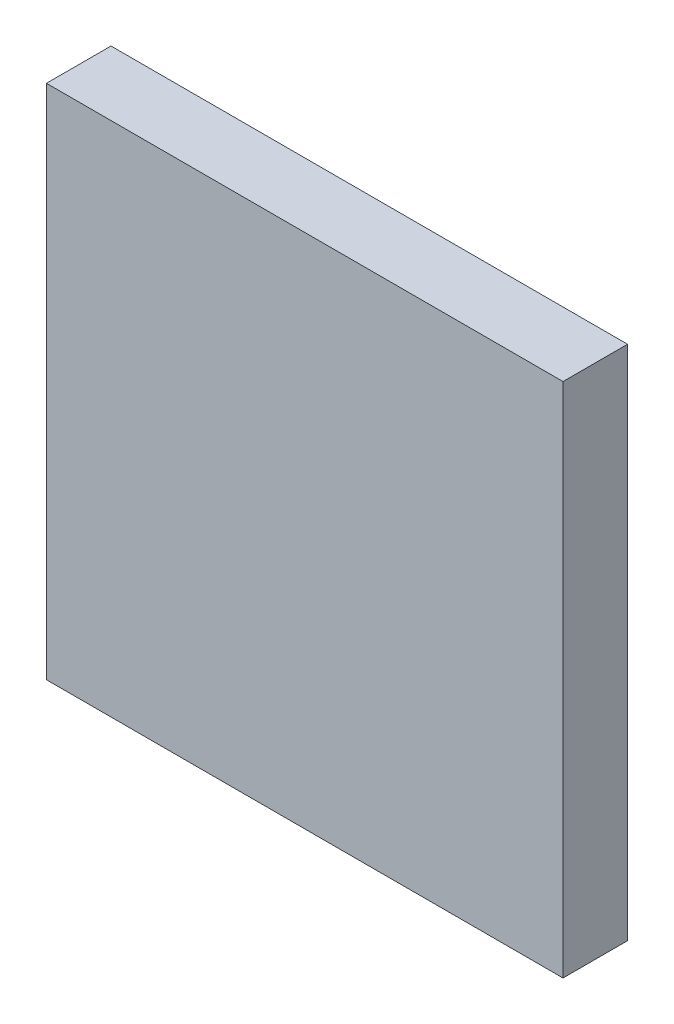
SolidWorks part; units mm, degrees
ref_plane "Plan de face" through (0, 0, 0) normal (0, 0, 1) x (1, 0, 0)
ref_plane "Plan de dessus" through (0, 0, 0) normal (0, 1, 0) x (1, 0, 0)
ref_plane "Plan de droite" through (0, 0, 0) normal (1, 0, 0) x (0, 0, -1)
sketch "Esquisse1" plane through (0, 0, 0) normal (0, 0, 1) x (1, 0, 0)
  line L1 (0, 0) -> (16, 0)
  line L2 (0, 0) -> (0, 16)
  line L3 (0, 16) -> (16, 16)
  line L4 (16, 0) -> (16, 16)
  dimension "D1" = 16
  dimension "D2" = 16
extrude "Boss.-Extru.1" add sketch "Esquisse1" along normal blind 2
sketch "Esquisse2" plane through (0, 0, 0) normal (0, 0, -1) x (-1, 0, 0)
  line L0 (0, 16) -> (0, 0) construction
  line L1 (-10, 10) -> (-6, 10)
  line L2 (-10, 10) -> (-10, 6)
  line L3 (-10, 6) -> (-6, 6)
  line L4 (-6, 10) -> (-6, 6)
  line L5 (0, 0) -> (-16, 0) construction
  dimension "D1" = 4
  dimension "D2" = 4
  dimension "D3" = 6
  dimension "D4" = 6
extrude "Boss.-Extru.2" add sketch "Esquisse2" along normal blind 4
